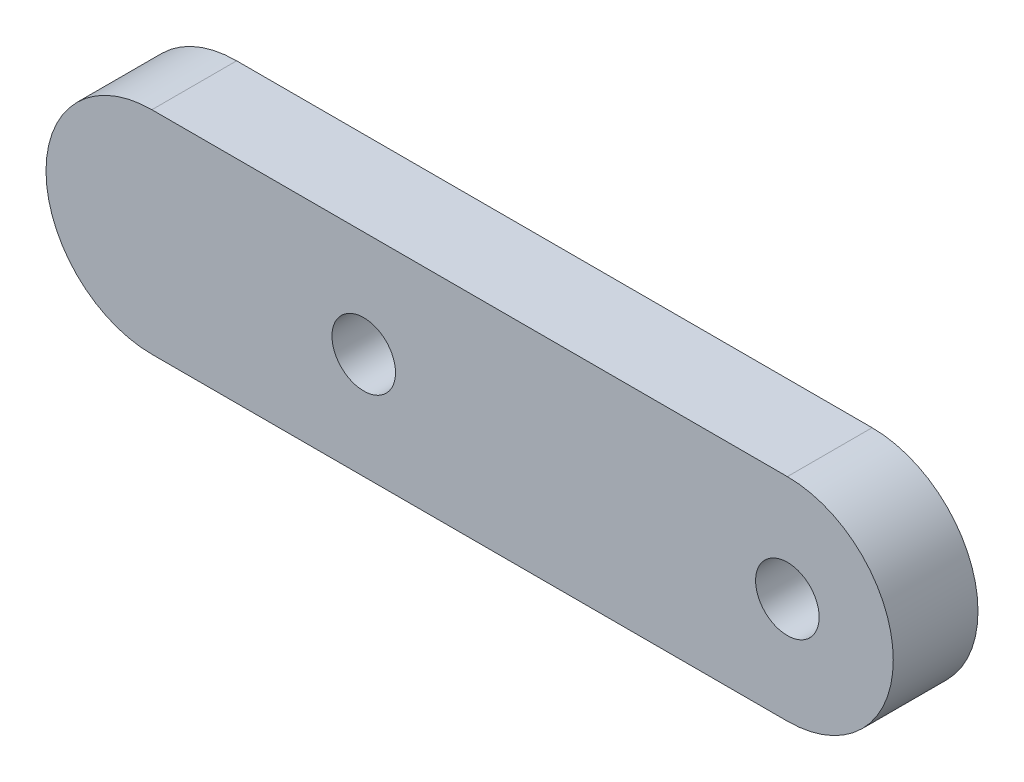
SolidWorks part; units mm, degrees
ref_plane "Plan de face" through (0, 0, 0) normal (0, 0, 1) x (1, 0, 0)
ref_plane "Plan de dessus" through (0, 0, 0) normal (0, 1, 0) x (1, 0, 0)
ref_plane "Plan de droite" through (0, 0, 0) normal (1, 0, 0) x (0, 0, -1)
sketch "Esquisse1" plane through (0, 0, 0) normal (0, 0, 1) x (1, 0, 0)
  line L0 (0, 5) -> (0, 0) construction
  line L1 (0, 0) -> (15, 0) construction
  line L2 (-15, 5) -> (15, 5)
  line L3 (-15, -5) -> (15, -5)
  circle A0 centre (15, 0) radius 1.5
  arc A1 (15, 5) -> (15, -5) centre (15, 0) cw
  arc A2 (-15, 5) -> (-15, -5) centre (-15, 0) ccw
  circle A3 centre (-5, 0) radius 1.5
  point P16 (0, -5)
  dimension "D1" = 30
  dimension "D2" = 5
  dimension "D3" = 3
  dimension "D4" = 3
  dimension "D5" = 20
extrude "Boss.-Extru.1" add sketch "Esquisse1" along normal blind 4
